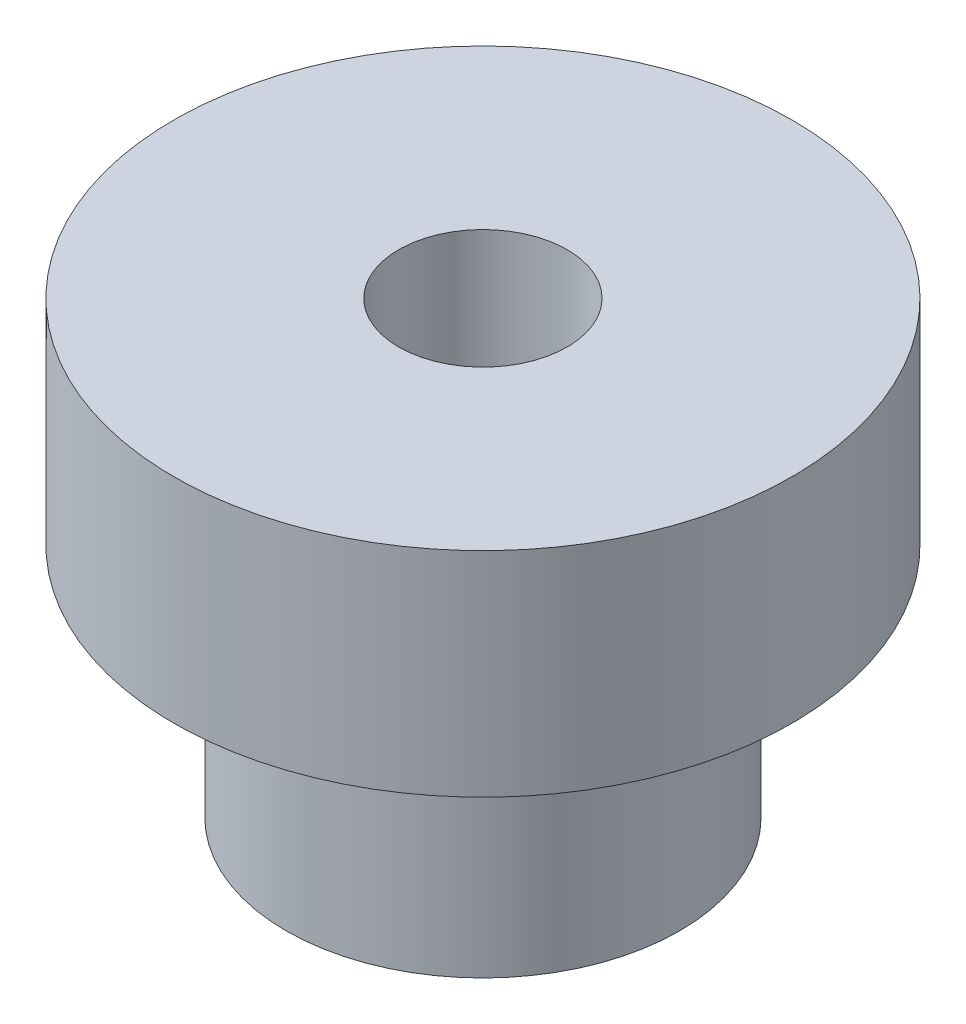
SolidWorks part; units mm, degrees
ref_plane "Front Plane" through (0, 0, 0) normal (0, 0, 1) x (1, 0, 0)
ref_plane "Top Plane" through (0, 0, 0) normal (0, 1, 0) x (1, 0, 0)
ref_plane "Right Plane" through (0, 0, 0) normal (1, 0, 0) x (0, 0, -1)
sketch "Sketch1" plane through (0, 0, 0) normal (0, 1, 0) x (1, 0, 0)
  circle A0 centre (0, 0) radius 5.5
extrude "Boss-Extrude1" add sketch "Sketch1" along normal blind 3.8
sketch "Sketch2" plane through (0, 0, 0) normal (0, -1, 0) x (1, 0, 0)
  circle A0 centre (0, 0) radius 3.5
extrude "Boss-Extrude2" add sketch "Sketch2" along normal blind 4.2
sketch "Sketch3" plane through (0, 3.8, 0) normal (0, 1, 0) x (1, 0, 0)
  circle A0 centre (0, 0) radius 1.5
extrude "Cut-Extrude1" cut sketch "Sketch3" against normal through all
